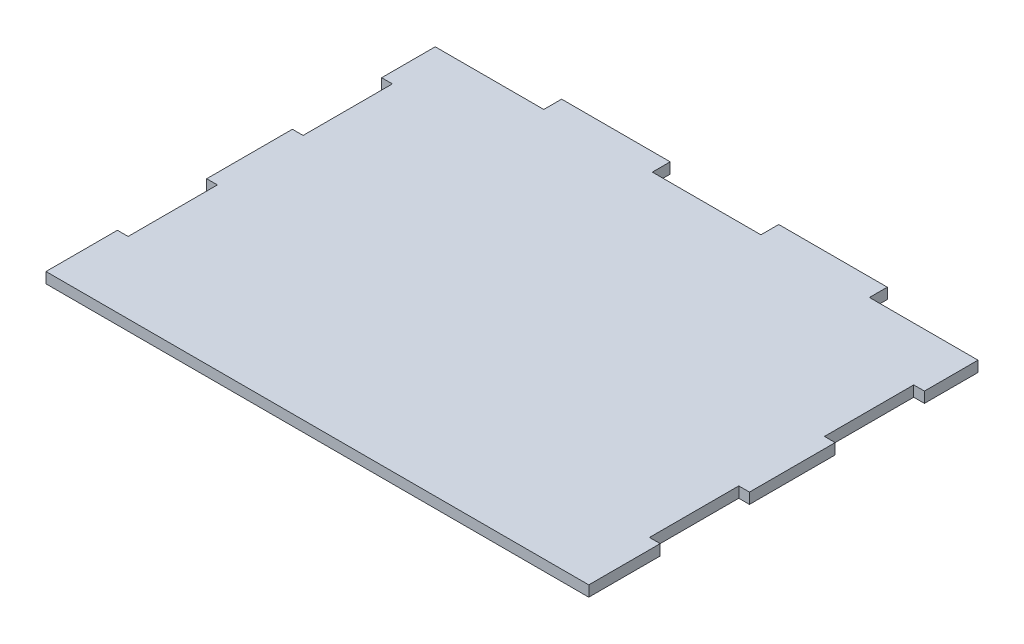
SolidWorks part; units mm, degrees
ref_plane "Front Plane" through (0, 0, 0) normal (0, 0, 1) x (1, 0, 0)
ref_plane "Top Plane" through (0, 0, 0) normal (0, 1, 0) x (1, 0, 0)
ref_plane "Right Plane" through (0, 0, 0) normal (1, 0, 0) x (0, 0, -1)
sketch "Sketch1" plane through (0, 0, 0) normal (0, 1, 0) x (1, 0, 0)
  line L0 (76, -57) -> (0, -57) construction
  line L2 (-76, -57) -> (-76, 57) construction
  line L3 (-76, 57) -> (76, 57) construction
  line L4 (76, -57) -> (76, 57) construction
  line L5 (0, 52) -> (0, -57)
  line L6 (-76, 0) -> (76, 0) construction
  line L7 (0, -57) -> (-76, -57)
  line L8 (-76, -57) -> (-76, -37)
  line L9 (-76, -37) -> (-73, -37)
  line L10 (-73, -37) -> (-73, -12)
  line L11 (-73, -12) -> (-76, -12)
  line L13 (-76, 52) -> (-45.6, 52)
  line L14 (-45.6, 52) -> (-45.6, 57)
  line L15 (-45.6, 57) -> (-15.2, 57)
  line L16 (-15.2, 57) -> (-15.2, 52)
  line L17 (-15.2, 52) -> (0, 52)
  line L18 (0, 52) -> (0, 57) construction
  line L19 (-76, -12) -> (-76, 12)
  line L20 (-76, 12) -> (-73, 12)
  line L21 (-73, 12) -> (-73, 37)
  line L22 (-73, 37) -> (-76, 37)
  line L23 (-76, 37) -> (-76, 52)
  point P76 (0, 0)
  dimension "D1" = 114
  dimension "D2" = 152
  dimension "D3" = 3
  dimension "D5" = 5
  dimension "D6" = 30.4
  dimension "D7" = 30.4
  dimension "D4" = 20
  dimension "D9" = 25
  dimension "D8" = 20
extrude "Boss-Extrude1" add sketch "Sketch1" along normal blind 3
mirror "Mirror1" about plane through (0, 3, -52) normal (-1, 0, 0) of "Boss-Extrude1"
equation "\"3mm akryyli\"= 3mm"
equation "\"5mm akryyli\"= 5mm"
equation "\"D3@Sketch1\"=\"3mm akryyli\""
equation "\"D5@Sketch1\"=\"5mm akryyli\""
equation "\"D1@Boss-Extrude1\"=\"3mm akryyli\""
